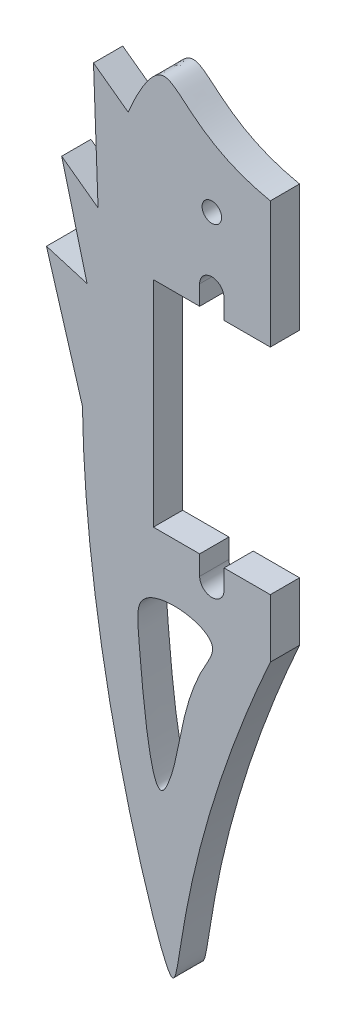
SolidWorks part; units mm, degrees
ref_plane "Front Plane" through (0, 0, 0) normal (0, 0, 1) x (1, 0, 0)
ref_plane "Top Plane" through (0, 0, 0) normal (0, 1, 0) x (1, 0, 0)
ref_plane "Right Plane" through (0, 0, 0) normal (1, 0, 0) x (0, 0, -1)
sketch "Sketch1" plane through (0, 0, 0) normal (0, 0, 1) x (1, 0, 0)
  line L0 (6, -11) -> (6, -17)
  line L1 (-6, 11) -> (6, 11)
  line L2 (-6, 11) -> (-6, -11)
  line L3 (-6, -11) -> (6, -11)
  line L5 (-6, 11) -> (6, -11) construction
  line L6 (-6, -11) -> (6, 11) construction
  line L7 (6, 11) -> (6, 24)
  line L8 (0, 0) -> (0, 33.3162) construction
  circle A0 centre (0, 20) radius 2.5
  spline S0 degree 3 poles (6, 24) (-2.0354, 25.6483) (-4.3647, 33.4726) (-18.0879, 6.0454) (-10.7598, -32.9789) (-2.444, -55.6348) (-4.1022, -39.4668) (6, -17) knots 0 0 0 0 0.114542 0.190676 0.697935 0.785208 1 1 1 1
  point P0 (0, 0)
  dimension "D6" = 5
  dimension "D1" = 12
  dimension "D2" = 22
  dimension "D3" = 6
  dimension "D4" = 13
  dimension "D5" = 9
extrude "Boss-Extrude1" add sketch "Sketch1" along normal blind 3 contours L7 S0 L0 L3 L2 L1
sketch "Sketch2" plane through (0, 0, 3) normal (0, 0, 1) x (1, 0, 0)
  line L0 (0, 22.3795) -> (0, 4.6389) construction
  line L1 (-6, 11) -> (6, 11) construction
  line L2 (0, 15.8198) -> (0, -14.7358) construction
  line L3 (-6, -11) -> (6, -11) construction
  line L4 (1.25, 13) -> (1.25, 11)
  line L5 (1.25, 11) -> (-1.25, 11)
  line L6 (-1.25, 11) -> (-1.25, 13)
  line L7 (-1.25, -13) -> (-1.25, -11)
  line L8 (-1.25, -11) -> (1.25, -11)
  line L9 (1.25, -11) -> (1.25, -13)
  circle A0 centre (0, 20) radius 1
  arc A1 (1.25, 13) -> (-1.25, 13) centre (0, 13) ccw
  arc A2 (-1.25, -13) -> (1.25, -13) centre (0, -13) ccw
  spline S0 degree 3 poles (-6.1046, -36.1228) (-3.1859, -30.6411) (-3.3695, -24.6597) (1.6138, -17.0271) (-7.932, -15.9366) (-7.1983, -25.7533) (-6.1046, -36.1228) (-3.1859, -30.6411) (-3.3695, -24.6597) knots -0.413876 -0.35383 -0.039314 0 0.359584 0.42027 0.586124 0.64617 0.960686 1 1.359584 1.42027 1.586124 only from (-4.5136, -33.0813) to (-4.5136, -33.0813)
  dimension "D1" = 2
  dimension "D3" = 2.5
  dimension "D2" = 9
  dimension "D4" = 2
  dimension "D5" = 2
extrude "Cut-Extrude1" cut sketch "Sketch2" against normal blind 3
sketch "Sketch4" plane through (0, 0, 3) normal (0, 0, 1) x (1, 0, 0)
  line L0 (-8.5915, 24.5909) -> (-12.1448, 27.1889)
  line L1 (-12.1448, 27.1889) -> (-11.6766, 14.5343)
  line L2 (-11.6766, 14.5343) -> (-15.4099, 17.2639)
  line L3 (-15.4099, 17.2639) -> (-12.8054, 7.2441)
  line L4 (-12.8054, 7.2441) -> (-16.9722, 8.4813)
  line L5 (-16.9722, 8.4813) -> (-13.2785, -3.9036)
  spline S0 degree 3 poles (1531.2365, 1313.508) (-0.8931, -160.6817) (6.9359, 56.0582) (-18.0879, 6.0454) (-10.7598, -32.9789) (7.0125, -81.3986) (-58.4117, 287.6463) (1834.1118, 759.5657) knots -0.57473 -0.57473 -0.57473 -0.57473 0.114542 0.190676 0.697935 0.785208 1.920347 1.920347 1.920347 1.920347 only from (6, 24) to (6, -17) construction
  spline S1 degree 3 poles (-8.5915, 24.5909) (-8.8387, 24.0114) (-12.2599, 15.4162) (-13.4091, 5.418) (-13.2785, -3.9036) knots 0.17609 0.17609 0.17609 0.17609 0.190676 0.384252 0.384252 0.384252 0.384252
  spline M5 degree 3 poles (6, 24) (-2.0354, 25.6483) (-4.3647, 33.4726) (-18.0879, 6.0454) (-10.7598, -32.9789) (-2.444, -55.6348) (-4.1022, -39.4668) (6, -17) knots 0 0 0 0 0.114542 0.190676 0.697935 0.785208 1 1 1 1
extrude "Boss-Extrude2" add sketch "Sketch4" against normal blind 3 contours L2 L3 M5 | L0 L1 M5 | L4 L5 M5
